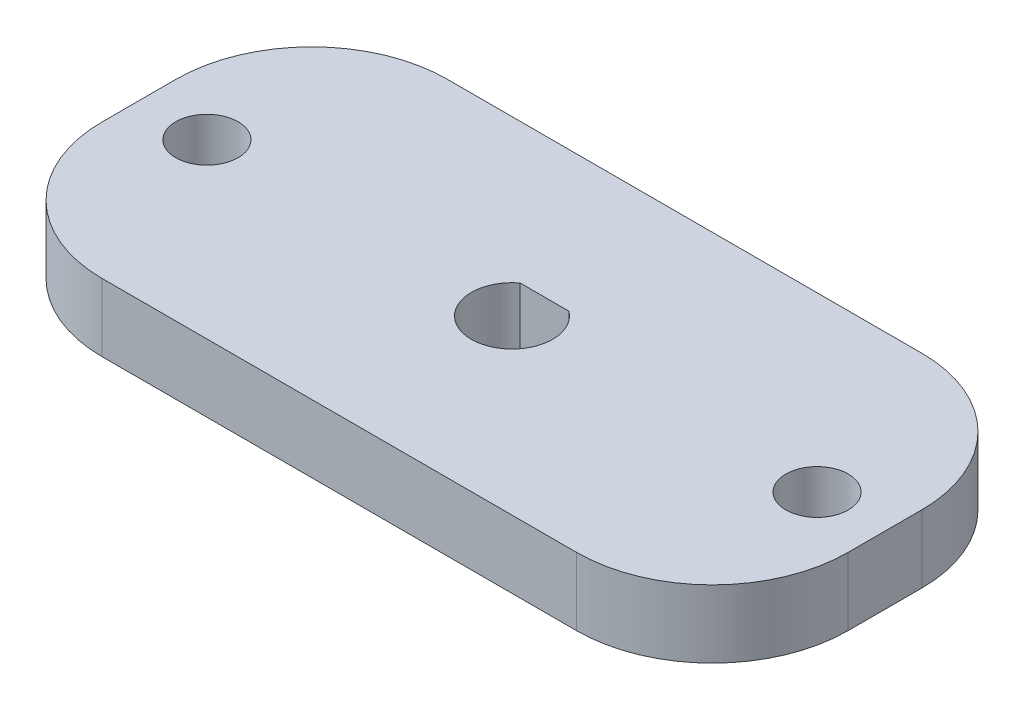
SolidWorks part; units mm, degrees
ref_plane "Płaszczyzna przednia" through (0, 0, 0) normal (0, 0, 1) x (1, 0, 0)
ref_plane "Płaszczyzna górna" through (0, 0, 0) normal (0, 1, 0) x (1, 0, 0)
ref_plane "Płaszczyzna prawa" through (0, 0, 0) normal (1, 0, 0) x (0, 0, -1)
sketch "Szkic1" plane through (0, 0, 0) normal (0, 1, 0) x (1, 0, 0)
  line L0 (-1.8, 2.4) -> (1.8, 2.4)
  line L1 (-17.5, -12.7261) -> (17.5, -12.7261)
  line L2 (-27.5, -2.7261) -> (-27.5, 2.7261)
  line L3 (-17.5, 12.7261) -> (17.5, 12.7261)
  line L4 (27.5, -2.7261) -> (27.5, 2.7261)
  line L5 (0, 12.7261) -> (0, -12.7261) construction
  line L6 (-27.5, 0) -> (27.5, 0) construction
  circle A0 centre (-22.5, 0) radius 2.3
  circle A1 centre (22.5, 0) radius 2.3
  arc A2 (-1.8, 2.4) -> (1.8, 2.4) centre (0, 0) ccw
  arc A3 (17.5, 12.7261) -> (27.5, 2.7261) centre (17.5, 2.7261) cw
  arc A4 (17.5, -12.7261) -> (27.5, -2.7261) centre (17.5, -2.7261) ccw
  arc A5 (-17.5, -12.7261) -> (-27.5, -2.7261) centre (-17.5, -2.7261) cw
  arc A6 (-27.5, 2.7261) -> (-17.5, 12.7261) centre (-17.5, 2.7261) cw
  point P0 (0, 0)
  dimension "D2" = 4.6
  dimension "D3" = 45
  dimension "D4" = 6
  dimension "D5" = 10
  dimension "D1" = 55
  dimension "D6" = 3.6
extrude "Dodanie-wyciągnięcie1" add sketch "Szkic1" along normal blind 5
